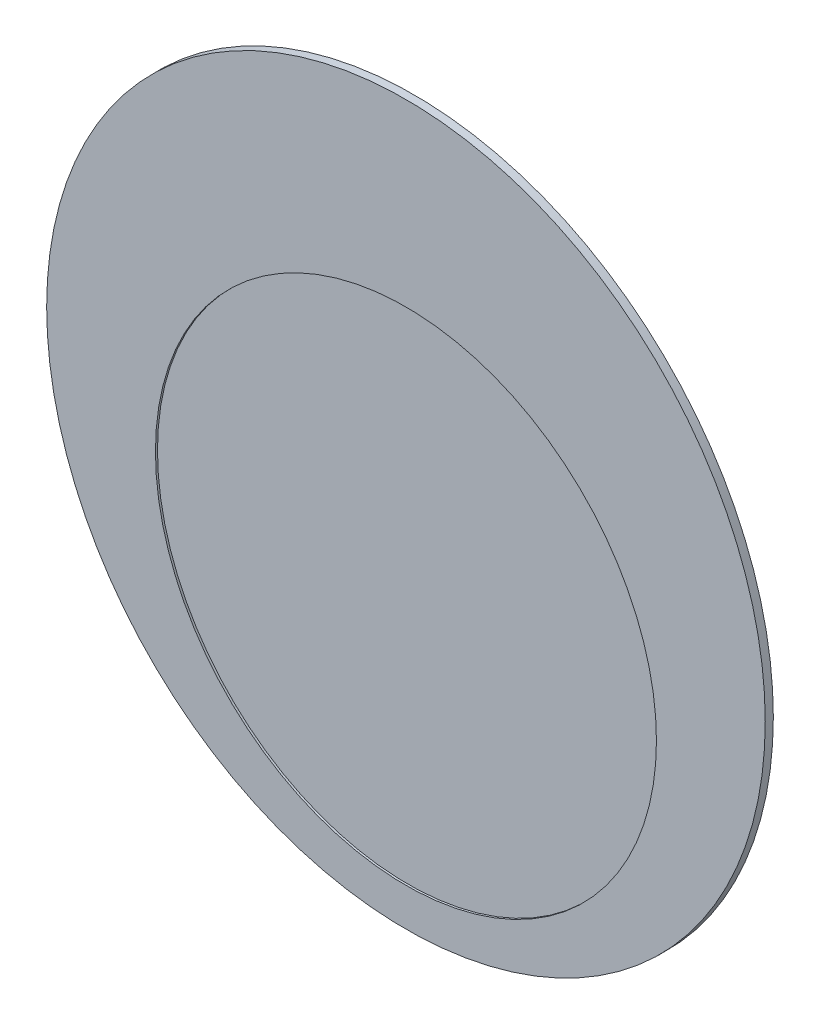
SolidWorks part; units mm, degrees
ref_plane "Front Plane" through (0, 0, 0) normal (0, 0, 1) x (1, 0, 0)
ref_plane "Top Plane" through (0, 0, 0) normal (0, 1, 0) x (1, 0, 0)
ref_plane "Right Plane" through (0, 0, 0) normal (1, 0, 0) x (0, 0, -1)
sketch "Sketch1" plane through (0, 0, 0) normal (0, 0, 1) x (1, 0, 0)
  circle A0 centre (0, 0) radius 35.5
  dimension "D1" = 71
extrude "Boss-Extrude1" add sketch "Sketch1" along normal blind 0.8
sketch "Sketch2" plane through (0, 0, 0.8) normal (0, 0, 1) x (1, 0, 0)
  line L0 (0, 0) -> (0, -7) construction
  circle A0 centre (0, -7) radius 24.75
  dimension "D2" = 49.5
  dimension "D1" = 7
extrude "Cut-Extrude1" cut sketch "Sketch2" against normal blind 0.2
